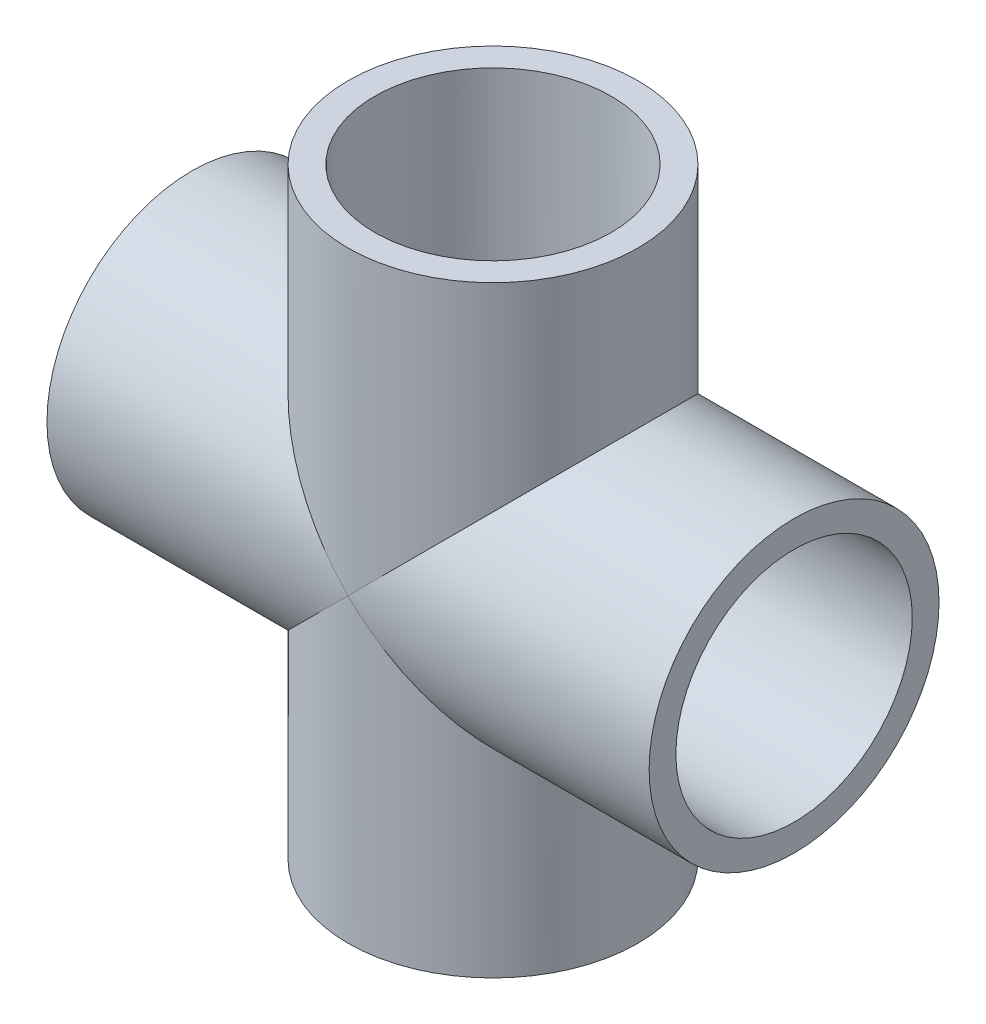
SolidWorks part; units mm, degrees
ref_plane "Front Plane" through (0, 0, 0) normal (0, 0, 1) x (1, 0, 0)
ref_plane "Top Plane" through (0, 0, 0) normal (0, 1, 0) x (1, 0, 0)
ref_plane "Right Plane" through (0, 0, 0) normal (1, 0, 0) x (0, 0, -1)
sketch "Sketch0" plane through (0, 0, 0) normal (0, 0, 1) x (1, 0, 0)
  line L0 (-42.8625, 0) -> (0, 0) construction
  line L1 (0, 0) -> (0, 42.8625) construction
  line L2 (-17.4625, 0) -> (0, 0) construction
  line L3 (0, 0) -> (0, 17.4625) construction
  line L4 (-42.8625, 20.6375) -> (-42.8625, -20.6375) construction
  line L5 (-17.4625, 16.637) -> (-42.8625, 16.8275) construction
  line L6 (-17.4625, 16.637) -> (-17.4625, -16.637) construction
  line L7 (-17.4625, -16.637) -> (-42.8625, -16.8275) construction
  line L8 (-42.8625, 16.8275) -> (-42.8625, -16.8275) construction
  line L9 (-20.6375, 42.8625) -> (20.6375, 42.8625) construction
  line L10 (-16.8275, 42.8625) -> (16.8275, 42.8625) construction
  line L11 (16.8275, 42.8625) -> (16.637, 17.4625) construction
  line L12 (16.637, 17.4625) -> (-16.637, 17.4625) construction
  line L13 (-16.637, 17.4625) -> (-16.8275, 42.8625) construction
  line L14 (-17.4625, 13.3223) -> (-17.4625, -13.3223) construction
  line L15 (-42.8625, 0) -> (-17.4625, 0) construction
  line L16 (0, 42.8625) -> (0, 17.4625) construction
  line L17 (0, 0) -> (17.4625, 0) construction
  line L18 (-13.3223, 17.4625) -> (13.3223, 17.4625) construction
  line L19 (17.4625, 0) -> (42.8625, 0) construction
  line L20 (0, 0) -> (0, -17.4625) construction
  line L21 (0, -17.4625) -> (0, -42.8625) construction
  dimension "H" = 42.8625
  dimension "G" = 17.4625
  dimension "M" = 41.275
  dimension "OD A" = 33.655
  dimension "OD B" = 33.274
  dimension "ID" = 26.6446
sketch "Sketch1" plane through (0, 0, 0) normal (0, 0, 1) x (1, 0, 0)
  line L0 (-42.8625, 0) -> (0, 0) construction
  line L1 (-42.8625, 0) -> (0, 0) construction
  line L2 (0, 0) -> (0, -20.6375) construction
  line L3 (-42.8625, -20.6375) -> (-17.4625, -20.6375)
  line L4 (-42.8625, -20.6375) -> (-42.8625, -16.8275)
  line L5 (-42.8625, -16.8275) -> (-17.4625, -16.637)
  line L6 (-17.4625, -20.6375) -> (-17.4625, -16.637)
  line L7 (-17.4625, -20.6375) -> (0, -20.6375) construction
  line L8 (42.8625, -16.8275) -> (17.4625, -16.637)
  line L9 (42.8625, -20.6375) -> (42.8625, -16.8275)
  line L10 (17.4625, -20.6375) -> (17.4625, -16.637)
  line L11 (42.8625, -20.6375) -> (17.4625, -20.6375)
revolve "Revolve1" add sketch "Sketch1" angle 360 about L1
sketch "Sketch2" plane through (0, 0, 0) normal (0, 0, 1) x (1, 0, 0)
  line L0 (16.8275, 42.8625) -> (16.637, 17.4625)
  line L1 (16.637, 17.4625) -> (20.6375, 17.4625)
  line L2 (20.6375, 17.4625) -> (20.6375, 42.8625)
  line L3 (20.6375, 42.8625) -> (16.8275, 42.8625)
  line L4 (0, 0) -> (0, 42.8625) construction
  line L5 (0, 0) -> (0, 42.8625) construction
  line L6 (0, 0) -> (17.4625, 0) construction
  line L7 (20.6375, -42.8625) -> (16.8275, -42.8625)
  line L8 (20.6375, -17.4625) -> (20.6375, -42.8625)
  line L9 (16.637, -17.4625) -> (20.6375, -17.4625)
  line L10 (16.8275, -42.8625) -> (16.637, -17.4625)
revolve "Revolve2" add sketch "Sketch2" angle 360 about L5
sketch "Sketch3" plane through (-17.4625, 0, 0) normal (1, 0, 0) x (0, 0, -1)
  circle A0 centre (0, 0) radius 13.3223
  circle A1 centre (0, 0) radius 20.6375
sketch "Sketch4" plane through (-17.4625, 0, 0) normal (1, 0, 0) x (0, 0, -1)
  circle A0 centre (0, 0) radius 20.6375 construction
  circle A1 centre (0, 0) radius 20.6375
extrude "Boss-Extrude1" add sketch "Sketch4" along normal up to vertex
sketch "Sketch5" plane through (0, 17.4625, 0) normal (0, -1, 0) x (1, 0, 0)
  circle A0 centre (0, 0) radius 20.6375 construction
  circle A1 centre (0, 0) radius 20.6375
extrude "Boss-Extrude2" add sketch "Sketch5" along normal up to vertex (34.925 mm away) up to point (0, -17.4625, 0)
sketch "Sketch6" plane through (0, 0, 0) normal (0, 0, 1) x (1, 0, 0)
  line L0 (-42.8625, -16.8275) -> (-17.4625, -16.637)
  line L1 (-17.4625, -16.637) -> (-17.4625, -13.3223)
  line L2 (-17.4625, -13.3223) -> (17.4625, -13.3223)
  line L3 (17.4625, -12.4829) -> (17.4625, 12.4829) construction
  line L4 (0, -13.3223) -> (0, 0) construction
  line L5 (17.4625, -16.637) -> (17.4625, -13.3223)
  line L6 (42.8625, -16.8275) -> (42.8625, 16.8275) construction
  line L7 (42.8625, -20.6375) -> (42.8625, 20.6375) construction
  line L8 (42.8625, -16.8275) -> (42.8625, 0)
  line L9 (42.8625, 0) -> (-42.8625, 0)
  line L10 (-42.8625, 0) -> (-42.8625, -16.8275)
  line L11 (42.8625, -16.8275) -> (17.4625, -16.637)
revolve "Cut-Revolve1" cut sketch "Sketch6" angle 360 about L9
sketch "Sketch7" plane through (0, 0, 0) normal (0, 0, 1) x (1, 0, 0)
  line L0 (16.8275, 42.8625) -> (16.637, 17.4625)
  line L1 (16.637, 17.4625) -> (13.3223, 17.4625)
  line L2 (13.3223, 17.4625) -> (13.3223, -17.4625)
  line L4 (13.3223, 0) -> (0, 0) construction
  line L5 (0, 42.8625) -> (0, -42.8625)
  line L6 (-20.6375, 42.8625) -> (20.6375, 42.8625) construction
  line L7 (0, 42.8625) -> (16.8275, 42.8625)
  line L8 (16.637, -17.4625) -> (13.3223, -17.4625)
  line L9 (16.8275, -42.8625) -> (16.637, -17.4625)
  line L10 (0, 0) -> (17.4625, 0) construction
  line L11 (0, -42.8625) -> (16.8275, -42.8625)
revolve "Cut-Revolve2" cut sketch "Sketch7" angle 360 about L5
